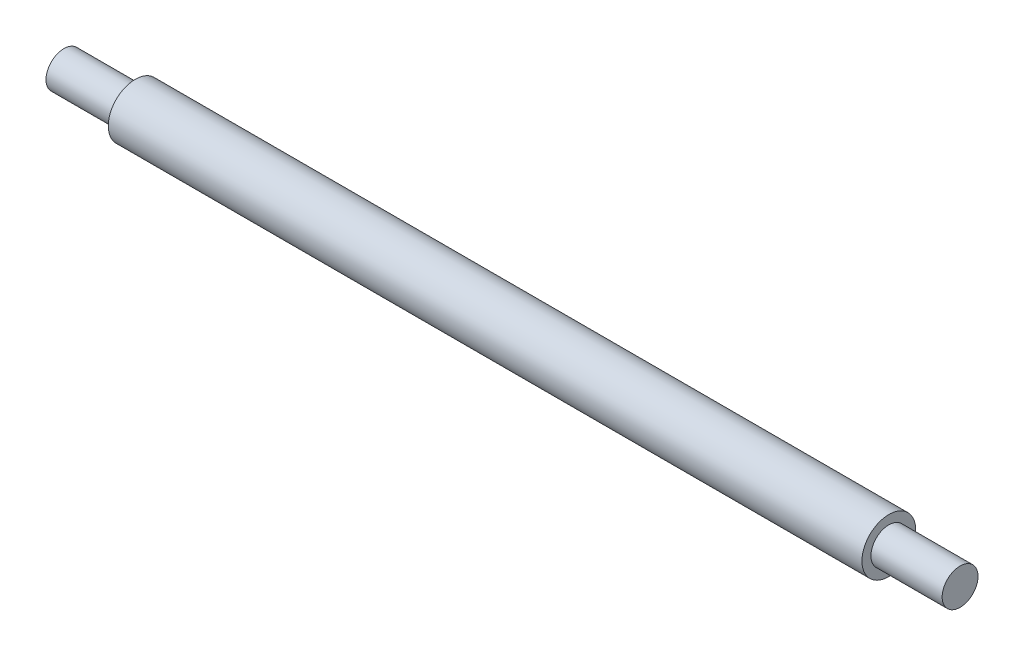
SolidWorks part; units mm, degrees
ref_plane "Front Plane" through (0, 0, 0) normal (0, 0, 1) x (1, 0, 0)
ref_plane "Top Plane" through (0, 0, 0) normal (0, 1, 0) x (1, 0, 0)
ref_plane "Right Plane" through (0, 0, 0) normal (1, 0, 0) x (0, 0, -1)
sketch "Sketch1" plane through (0, 0, 0) normal (0, 0, 1) x (1, 0, 0)
  line L0 (0, 0) -> (0, 2)
  line L1 (0, 2) -> (7.94, 2)
  line L2 (7.94, 2) -> (7.94, 3)
  line L3 (7.94, 3) -> (91.94, 3)
  line L4 (91.94, 3) -> (91.94, 2)
  line L5 (91.94, 2) -> (99.88, 2)
  line L6 (99.88, 2) -> (99.88, 0)
  line L7 (-15.2814, 0) -> (122.0276, 0) construction
  line L8 (0, 0) -> (99.88, 0)
  dimension "D1" = 84
  dimension "D2" = 7.94
  dimension "D3" = 7.94
  dimension "D4" = 2
  dimension "D5" = 3
  dimension "D6" = 2
revolve "Revolve1" add sketch "Sketch1" angle 360 about L7
